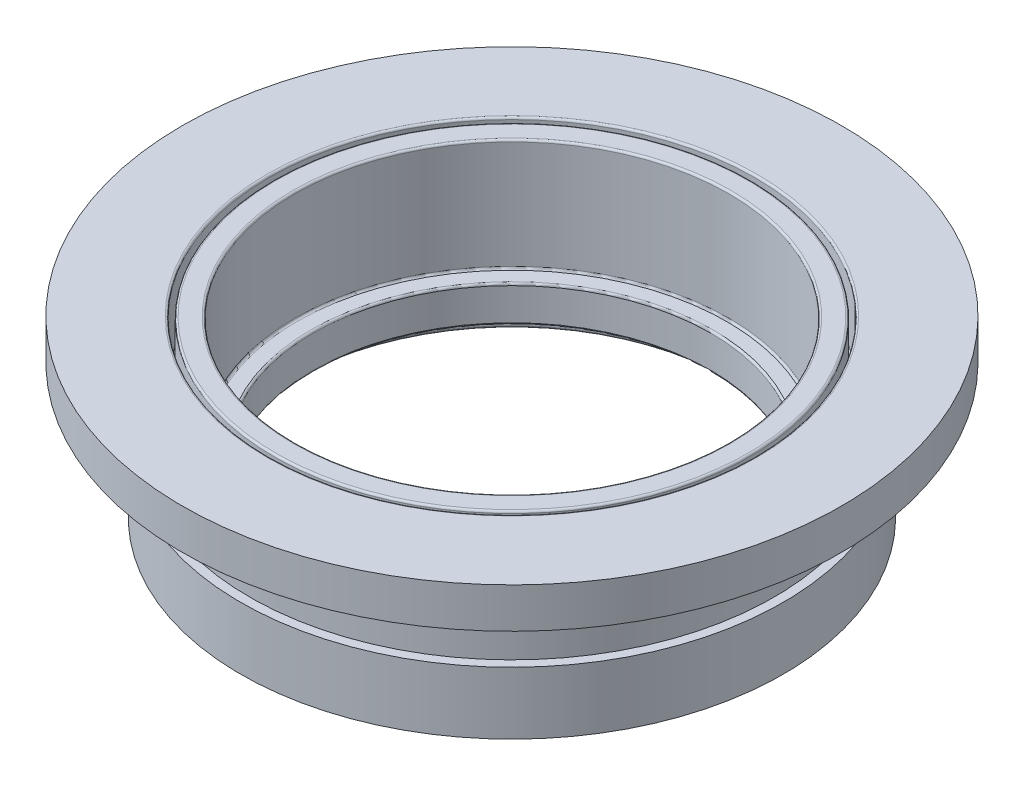
SolidWorks part; units mm, degrees
ref_plane "Front Plane" through (0, 0, 0) normal (0, 0, 1) x (1, 0, 0)
ref_plane "Top Plane" through (0, 0, 0) normal (0, 1, 0) x (1, 0, 0)
ref_plane "Right Plane" through (0, 0, 0) normal (1, 0, 0) x (0, 0, -1)
sketch "Sketch1" plane through (0, 0, 0) normal (0, 1, 0) x (1, 0, 0)
  line L0 (0, 34) -> (0, -30.8421) construction
  line L1 (27, 30.0881) -> (27, 26.0881)
  line L2 (27, 26.0881) -> (26.1, 26.0881)
  line L3 (26.1, 26.0881) -> (26.1, 22.8881)
  line L4 (26.1, 22.8881) -> (27, 22.8881)
  line L5 (27, 22.8881) -> (27, 16.6881)
  line L7 (27, 30.0881) -> (32.8, 30.0881)
  line L8 (32.8, 30.0881) -> (32.8, 34.0881)
  line L10 (25.2, 34.0881) -> (32.8, 34.0881)
  line L16 (22.5, 34) -> (21.8, 34)
  line L17 (21.6, 33.8) -> (21.6, 23.0881)
  line L31 (25.2, 32.6554) -> (25.2, 16.6881)
  line L32 (25.2, 16.6881) -> (27, 16.6881)
  line L37 (21.4, 22.8881) -> (20, 22.8881)
  line L38 (19.8, 22.6881) -> (19.8, 19.4881)
  line L39 (20, 19.2881) -> (21.4, 19.2881)
  line L40 (21.6, 19.0881) -> (21.6, 17.9594)
  line L41 (21.8, 17.7594) -> (22.5, 17.7594)
  line L42 (22.7, 17.9594) -> (22.7, 32.6554)
  line L43 (25.2, 34.0881) -> (24.4, 34.0881)
  line L44 (24.2, 33.8881) -> (24.2, 28.1554)
  line L46 (24.7, 27.6554) -> (24.7, 32.6554)
  line L47 (24.9, 32.8554) -> (25, 32.8554)
  line L48 (24.5, 27.4554) -> (23.4, 27.4554)
  line L49 (23.2, 27.6554) -> (23.2, 32.6554)
  line L50 (23, 32.8554) -> (22.9, 32.8554)
  line L52 (22.5, 34) -> (23.5, 34)
  line L53 (23.7, 33.8) -> (23.7, 28.1554)
  line L54 (23.9, 27.9554) -> (24, 27.9554)
  arc A0 (23.7, 28.1554) -> (23.9, 27.9554) centre (23.9, 28.1554) ccw
  arc A1 (22.5, 17.7594) -> (22.7, 17.9594) centre (22.5, 17.9594) ccw
  arc A2 (21.6, 17.9594) -> (21.8, 17.7594) centre (21.8, 17.9594) ccw
  arc A3 (21.4, 19.2881) -> (21.6, 19.0881) centre (21.4, 19.0881) cw
  arc A4 (19.8, 19.4881) -> (20, 19.2881) centre (20, 19.4881) ccw
  arc A5 (20, 22.8881) -> (19.8, 22.6881) centre (20, 22.6881) ccw
  arc A6 (21.4, 22.8881) -> (21.6, 23.0881) centre (21.4, 23.0881) ccw
  arc A7 (21.8, 34) -> (21.6, 33.8) centre (21.8, 33.8) ccw
  arc A8 (23.5, 34) -> (23.7, 33.8) centre (23.5, 33.8) cw
  arc A9 (22.9, 32.8554) -> (22.7, 32.6554) centre (22.9, 32.6554) ccw
  arc A10 (23.2, 32.6554) -> (23, 32.8554) centre (23, 32.6554) ccw
  arc A11 (23.4, 27.4554) -> (23.2, 27.6554) centre (23.4, 27.6554) cw
  arc A12 (24.5, 27.4554) -> (24.7, 27.6554) centre (24.5, 27.6554) ccw
  arc A13 (24, 27.9554) -> (24.2, 28.1554) centre (24, 28.1554) ccw
  arc A14 (25, 32.8554) -> (25.2, 32.6554) centre (25, 32.6554) cw
  arc A15 (24.7, 32.6554) -> (24.9, 32.8554) centre (24.9, 32.6554) cw
  arc A16 (24.4, 34.0881) -> (24.2, 33.8881) centre (24.4, 33.8881) ccw
  point P9 (0, 0)
  point P49 (19.8, 22.8881)
  point P52 (21.6, 22.8881)
  point P55 (21.6, 34)
  dimension "D14" = 0.2
  dimension "D1" = 4
  dimension "D2" = 4
  dimension "D3" = 3.2
  dimension "D4" = 0.9
  dimension "D5" = 1.8
  dimension "D6" = 1.8
  dimension "D7" = 0.9
  dimension "D8" = 0.5
  dimension "D9" = 7.6
  dimension "D10" = 0.5
  dimension "D11" = 0.5
  dimension "D12" = 0.5
  dimension "D13" = 0.5
  dimension "D15" = 6.2
  dimension "D16" = 4.5
  dimension "D17" = 0.5
  dimension "D18" = 27
revolve "Revolve1" add sketch "Sketch1" angle 360 about L0
sketch "Sketch3" plane through (0, 0, 0) normal (0, 1, 0) x (1, 0, 0)
  line L0 (-32.3965, 0) -> (36.1703, 0) construction
move or copy body "Body-Move/Copy1" bodies to move or copy 101 copy no rotation origin (0, 0, 0) rotation axis (1, 0, 0) rotation angle 90 parameters "Angle Around Edge"=90
